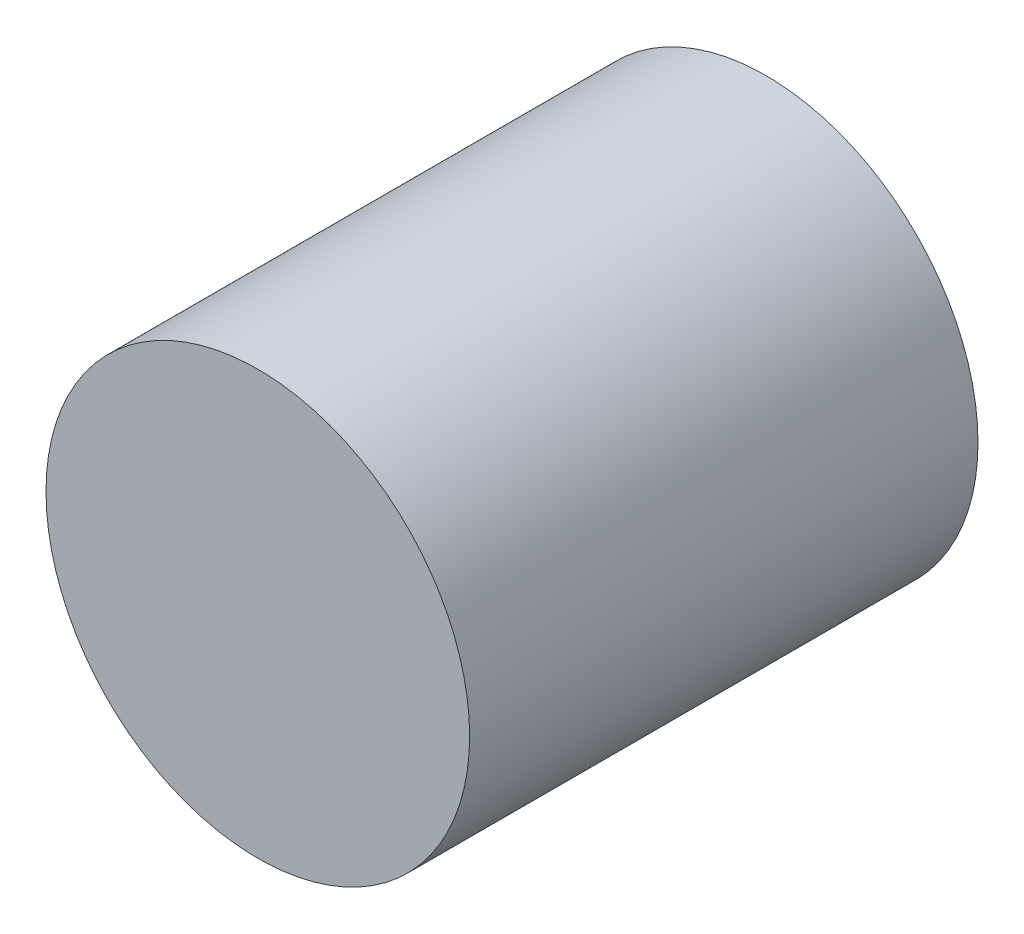
SolidWorks part; units mm, degrees
ref_plane "Plan de face" through (0, 0, 0) normal (0, 0, 1) x (1, 0, 0)
ref_plane "Plan de dessus" through (0, 0, 0) normal (0, 1, 0) x (1, 0, 0)
ref_plane "Plan de droite" through (0, 0, 0) normal (1, 0, 0) x (0, 0, -1)
sketch "Esquisse1" plane through (0, 0, 0) normal (0, 0, 1) x (1, 0, 0)
  circle A0 centre (0, 0) radius 25
  dimension "D1" = 50
extrude "Boss.-Extru.1" add sketch "Esquisse1" along normal blind 60
